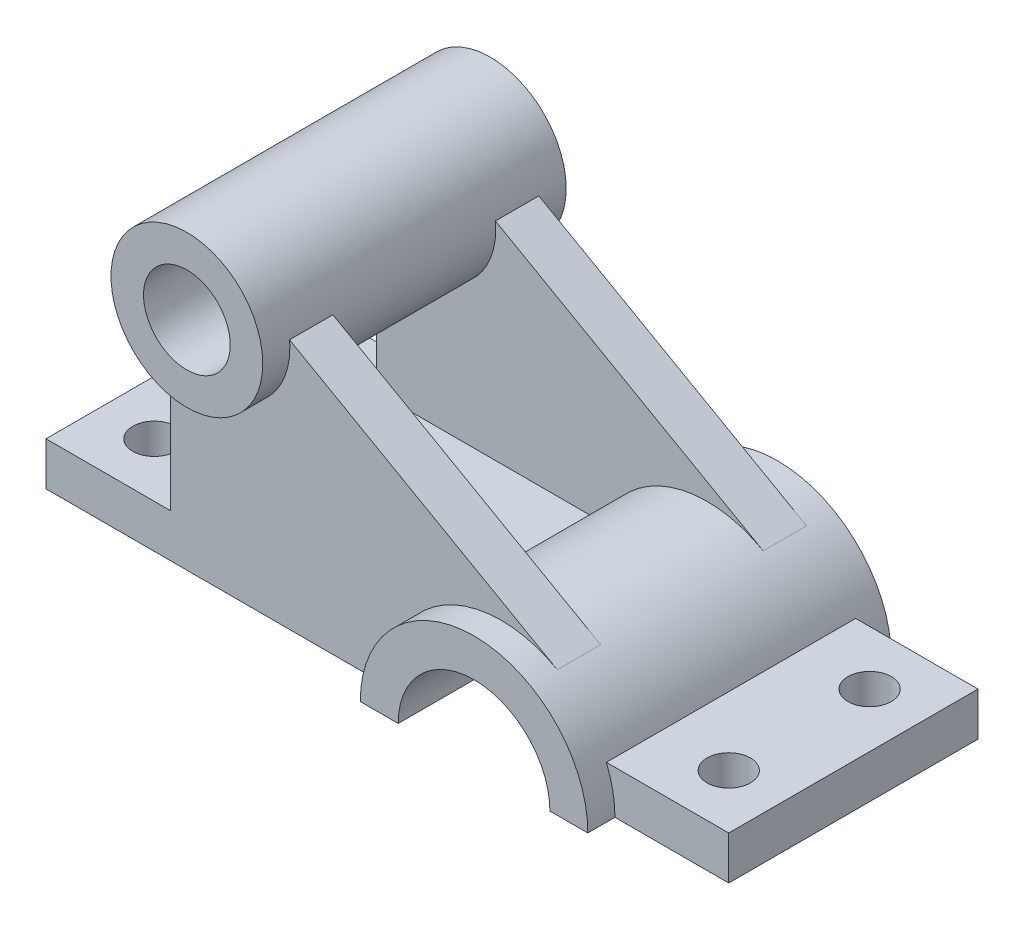
SolidWorks part; units mm, degrees
ref_plane "Front Plane" through (0, 0, 0) normal (0, 0, 1) x (1, 0, 0)
ref_plane "Top Plane" through (0, 0, 0) normal (0, 1, 0) x (1, 0, 0)
ref_plane "Right Plane" through (0, 0, 0) normal (1, 0, 0) x (0, 0, -1)
sketch "Sketch1" plane through (0, 0, 0) normal (0, 0, 1) x (1, 0, 0)
  line L0 (-21, 0) -> (-14, 0)
  line L1 (14, 0) -> (21, 0)
  arc A0 (21, 0) -> (-21, 0) centre (0, 0) ccw
  arc A1 (14, 0) -> (-14, 0) centre (0, 0) ccw
  dimension "D1" = 42
  dimension "D2" = 28
extrude "Boss-Extrude1" add sketch "Sketch1" along normal mid plane 56
sketch "Sketch2" plane through (0, 0, 0) normal (0, 0, 1) x (1, 0, 0)
  circle A0 centre (-53, 45) radius 14
  circle A1 centre (-53, 45) radius 8
  dimension "D1" = 28
  dimension "D2" = 16
  dimension "D3" = 53
  dimension "D4" = 45
extrude "Boss-Extrude2" add sketch "Sketch2" along normal mid plane 56 separate body
sketch "Sketch6" plane through (0, 0, 0) normal (0, 0, 1) x (1, 0, 0)
  line L0 (-84, 0) -> (-14, 0)
  line L1 (42, 0) -> (42, 8)
  line L2 (42, 8) -> (11.4891, 8)
  line L3 (-84, 8) -> (-84, 0)
  line L4 (-11.4891, 8) -> (-84, 8)
  line L5 (14, 0) -> (42, 0)
  arc A0 (14, 0) -> (-14, 0) centre (0, 0) ccw construction
  arc A1 (21, 0) -> (-21, 0) centre (0, 0) ccw construction
  arc A2 (14, 0) -> (11.4891, 8) centre (0, 0) ccw
  arc A3 (21, 0) -> (19.4165, 8) centre (0, 0) ccw
  arc A4 (-19.4165, 8) -> (-21, 0) centre (0, 0) ccw
  arc A5 (-11.4891, 8) -> (-14, 0) centre (0, 0) ccw
  point P15 (0, 0)
  dimension "D1" = 126
  dimension "D2" = 8
  dimension "D3" = 42
extrude "Boss-Extrude4" add sketch "Sketch6" along normal mid plane 46 contours L5 L1 L2 A2 | L0 A5 L4 L3
sketch "Sketch7" plane through (0, 0, 23) normal (0, 0, 1) x (1, 0, 0)
  line L0 (-61, 45) -> (-61, 8)
  line L1 (-19.4165, 8) -> (-84, 8) construction
  line L4 (-19.4165, 8) -> (-61, 8)
  line L5 (-49.0537, 51.9589) -> (10.359, 18.2672)
  circle A0 centre (-53, 45) radius 8 construction
  arc A1 (-61, 45) -> (-49.0537, 51.9589) centre (-53, 45) ccw
  arc A2 (21, 0) -> (-21, 0) centre (0, 0) ccw construction
  arc A3 (10.359, 18.2672) -> (-19.4165, 8) centre (0, 0) ccw
extrude "Boss-Extrude5" add sketch "Sketch7" against normal blind 8
mirror "Mirror1" about plane through (0, 0, 0) normal (0, 0, 1) of "Boss-Extrude5"
hole_wizard "Hole1" positions "Sketch8" profile "Sketch9" legacy end condition through all
sketch "Sketch8" plane through (0, 8, 0) normal (0, 1, 0) x (1, 0, 0)
  line L0 (42, -23) -> (42, 23) construction
  line L1 (0, 0) -> (51.9572, 0) construction
  point P0 (32, 13)
  point P2 (32, -13)
  point P12 (0, 0)
  dimension "D1" = 26
  dimension "D2" = 10
sketch "Sketch9" plane through (32, 8, -13) normal (1, 0, 0) x (0, 0, 1)
  line L0 (0, 0) -> (0, 8)
  line L1 (0, 8) -> (4, 8)
  line L2 (4, 8) -> (4, 0)
  line L3 (4, 0) -> (0, 0)
  line L4 (0, 110) -> (0, -10) construction
  dimension "Diameter" = 8
  dimension "Depth" = 8
hole_wizard "Hole2" positions "Sketch10" profile "Sketch11" legacy end condition through all
sketch "Sketch10" plane through (0, 8, 0) normal (0, 1, 0) x (1, 0, 0)
  line L0 (0, 0) -> (-114.1647, 0) construction
  line L2 (-84, -23) -> (-84, 23) construction
  point P0 (-74, -13)
  point P2 (-74, 13)
  point P9 (0, 0)
  point P14 (-75.5867, 12.0721)
  point P15 (0, 0)
  dimension "D1" = 26
  dimension "D2" = 10
sketch "Sketch11" plane through (-74, 8, 13) normal (1, 0, 0) x (0, 0, 1)
  line L0 (0, 0) -> (0, 8)
  line L1 (0, 8) -> (4, 8)
  line L2 (4, 8) -> (4, 0)
  line L3 (4, 0) -> (0, 0)
  line L4 (0, 110) -> (0, -10) construction
  dimension "Diameter" = 8
  dimension "Depth" = 8
